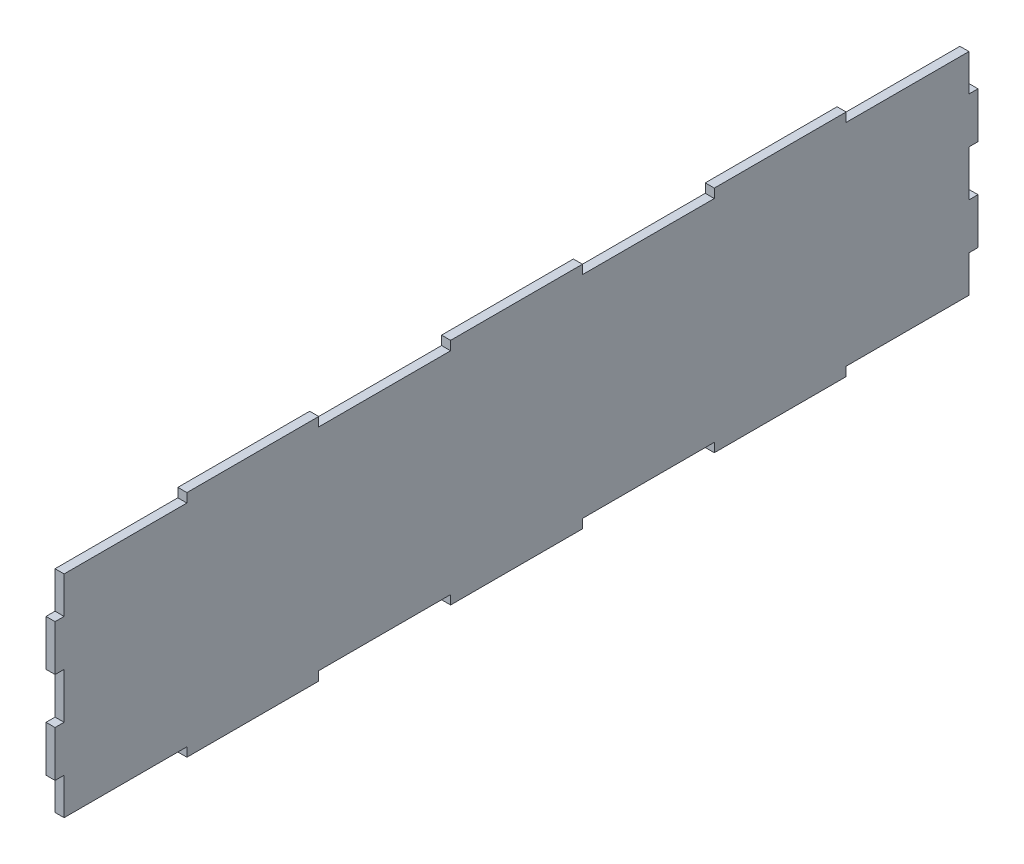
SolidWorks part; units mm, degrees
material "Pin"
ref_plane "Plan de face" through (0, 0, 0) normal (0, 0, 1) x (1, 0, 0)
ref_plane "Plan de dessus" through (0, 0, 0) normal (0, 1, 0) x (1, 0, 0)
ref_plane "Plan de droite" through (0, 0, 0) normal (1, 0, 0) x (0, 0, -1)
sketch "Esquisse3" plane through (0, 0, 0) normal (1, 0, 0) x (0, 0, -1)
  line L0 (109.2857, 38) -> (65.5714, 38)
  line L1 (150, 35) -> (109.2857, 35)
  line L3 (150, -35) -> (109.2857, -35)
  line L6 (109.2857, -38) -> (65.5714, -38)
  line L8 (109.2857, 38) -> (109.2857, 35)
  line L9 (65.5714, -38) -> (65.5714, -35)
  line L10 (21.8571, 38) -> (21.8571, 35)
  line L11 (-21.8571, -38) -> (-21.8571, -35)
  line L12 (-65.5714, 38) -> (-65.5714, 35)
  line L13 (-109.2857, -38) -> (-109.2857, -35)
  line L14 (109.2857, -35) -> (109.2857, -38)
  line L15 (65.5714, 35) -> (65.5714, 38)
  line L16 (21.8571, -35) -> (21.8571, -38)
  line L17 (-21.8571, 35) -> (-21.8571, 38)
  line L18 (-65.5714, -35) -> (-65.5714, -38)
  line L19 (-109.2857, 35) -> (-109.2857, 38)
  line L20 (-109.2857, -35) -> (-150, -35)
  line L21 (153, -38) -> (-153, -38) construction
  line L22 (-65.5714, -38) -> (-109.2857, -38)
  line L23 (150, -35) -> (-150, -35) construction
  line L24 (-21.8571, -35) -> (-65.5714, -35)
  line L25 (21.8571, -38) -> (-21.8571, -38)
  line L26 (65.5714, -35) -> (21.8571, -35)
  line L27 (153, -38) -> (109.2857, -38) construction
  line L28 (-109.2857, -38) -> (-153, -38) construction
  line L29 (65.5714, 35) -> (21.8571, 35)
  line L30 (153, 38) -> (-153, 38) construction
  line L31 (21.8571, 38) -> (-21.8571, 38)
  line L32 (150, 35) -> (-150, 35) construction
  line L33 (-21.8571, 35) -> (-65.5714, 35)
  line L34 (-65.5714, 38) -> (-109.2857, 38)
  line L35 (-109.2857, 35) -> (-150, 35)
  line L36 (109.2857, 38) -> (153, 38) construction
  line L37 (-109.2857, 38) -> (-153, 38) construction
  line L38 (153, -38) -> (-153, 38) construction
  line L43 (153, 38) -> (153, -38) construction
  line L45 (150, 35) -> (150, -35) construction
  line L49 (-153, 38) -> (-153, -38) construction
  line L51 (-150, 35) -> (-150, -35) construction
  line L53 (153, 22.8) -> (153, 7.6)
  line L59 (-153, -22.8) -> (-153, -7.6)
  line L65 (150, 35) -> (150, 22.8)
  line L66 (153, 22.8) -> (150, 22.8)
  line L67 (-153, 7.6) -> (-150, 7.6)
  line L68 (153, -7.6) -> (150, -7.6)
  line L69 (-153, -22.8) -> (-150, -22.8)
  line L70 (-150, 35) -> (-150, 22.8)
  line L71 (-150, 22.8) -> (-153, 22.8)
  line L72 (150, 7.6) -> (153, 7.6)
  line L73 (-150, -7.6) -> (-153, -7.6)
  line L74 (150, -22.8) -> (153, -22.8)
  line L75 (153, 38) -> (153, 22.8) construction
  line L76 (153, -22.8) -> (153, -38) construction
  line L77 (-153, 7.6) -> (-153, 22.8)
  line L78 (-150, 7.6) -> (-150, -7.6)
  line L79 (-150, -22.8) -> (-150, -35)
  line L80 (150, 7.6) -> (150, -7.6)
  line L81 (150, -22.8) -> (150, -35)
  line L82 (153, -7.6) -> (153, -22.8)
  point P48 (-153, 15.2)
  dimension "D1" = 300
  dimension "D2" = 70
  dimension "D4" = 306
  dimension "D3" = 3
extrude "Boss.-Extru.3" add sketch "Esquisse3" along normal blind 3
